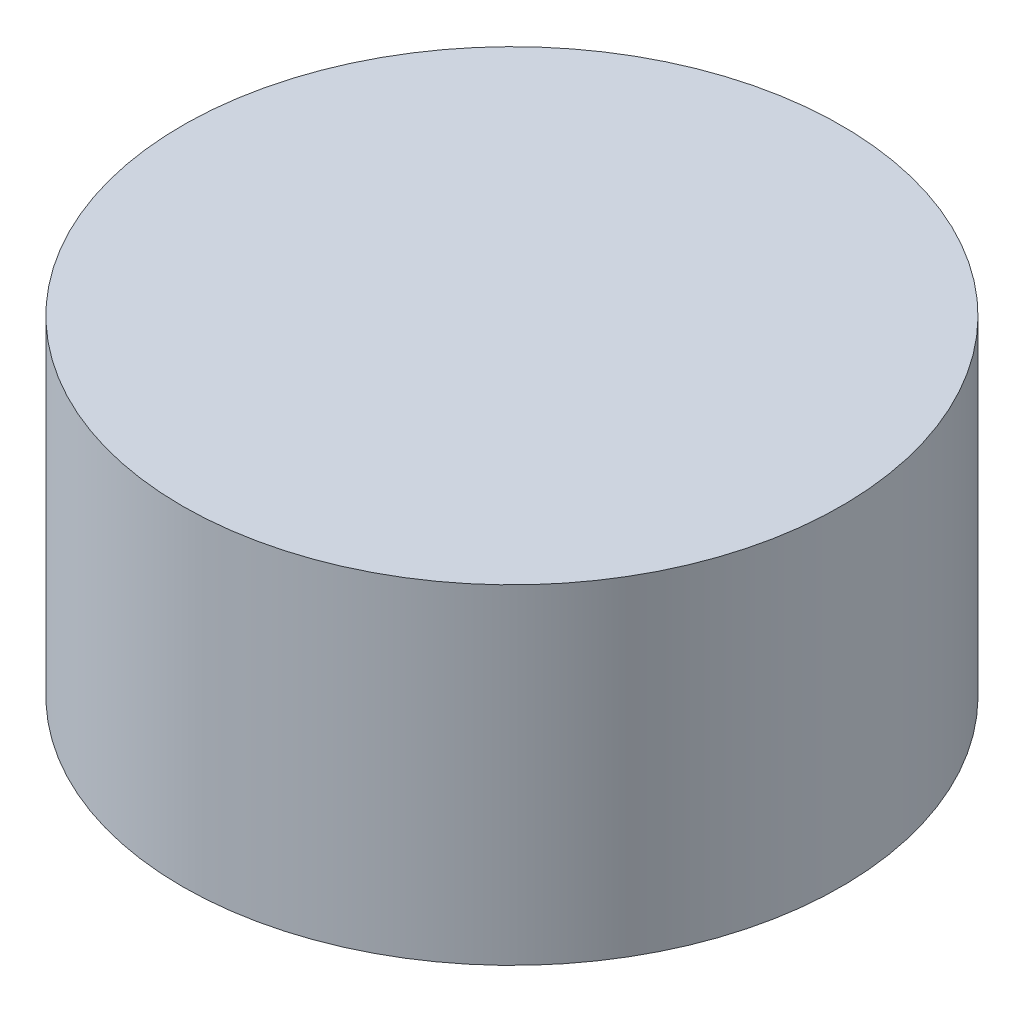
SolidWorks part; units mm, degrees
material "AISI 304"
ref_plane "Front Plane" through (0, 0, 0) normal (0, 0, 1) x (1, 0, 0)
ref_plane "Top Plane" through (0, 0, 0) normal (0, 1, 0) x (1, 0, 0)
ref_plane "Right Plane" through (0, 0, 0) normal (1, 0, 0) x (0, 0, -1)
sketch "Sketch1" plane through (0, 0, 0) normal (0, 1, 0) x (1, 0, 0)
  circle A0 centre (0, 0) radius 3
  dimension "D1" = 6
extrude "Boss-Extrude1" add sketch "Sketch1" along normal blind 3
